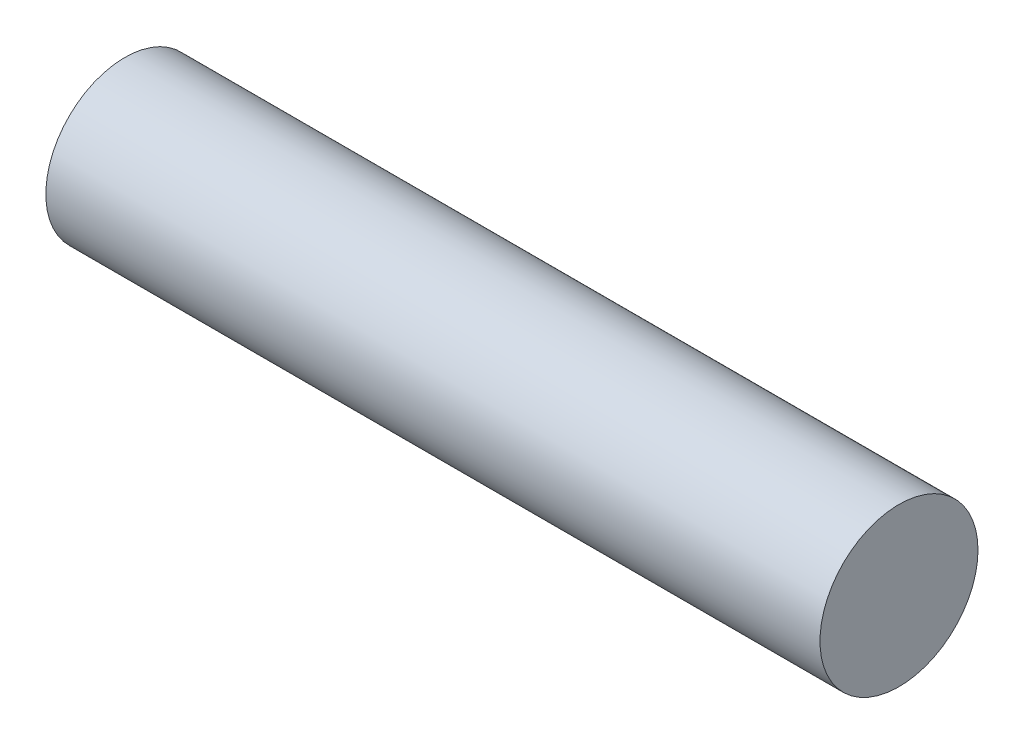
SolidWorks part; units mm, degrees
ref_plane "Front Plane" through (0, 0, 0) normal (0, 0, 1) x (1, 0, 0)
ref_plane "Top Plane" through (0, 0, 0) normal (0, 1, 0) x (1, 0, 0)
ref_plane "Right Plane" through (0, 0, 0) normal (1, 0, 0) x (0, 0, -1)
sketch "Sketch1" plane through (0, 0, 0) normal (1, 0, 0) x (0, 0, -1)
  circle A0 centre (0, 0) radius 31.75
  dimension "D1" = 63.5
extrude "Boss-Extrude1" add sketch "Sketch1" along normal blind 311.15
